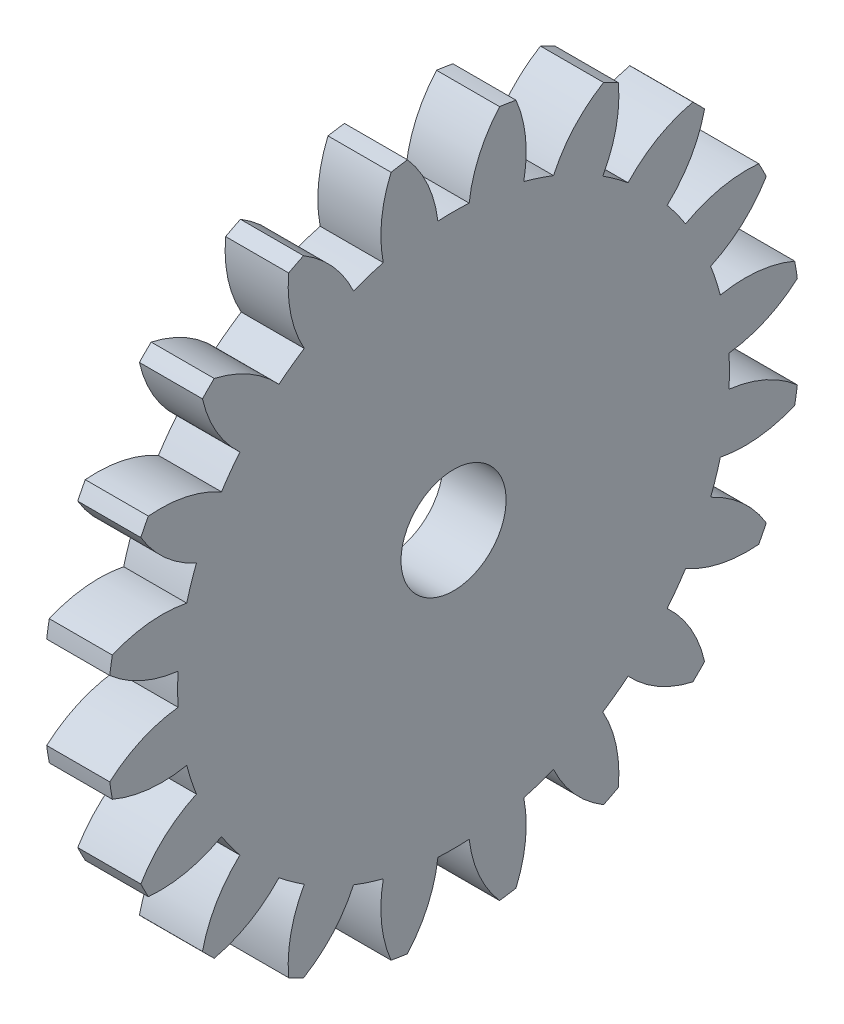
SolidWorks part; units mm, degrees
ref_plane "Plane1" through (0, 0, 0) normal (0, 0, 1) x (1, 0, 0)
ref_plane "Plane2" through (0, 0, 0) normal (0, 1, 0) x (1, 0, 0)
ref_plane "Plane3" through (0, 0, 0) normal (1, 0, 0) x (0, 0, -1)
sketch "HoldingSke" plane through (0, 0, 0) normal (0, 1, 0) x (1, 0, 0)
  line L0 (0, 0) -> (0.6265, -0.228)
  line L1 (-15, 0) -> (100, 0) construction
  line L2 (0, 0) -> (-2.1039, 2.3779)
  line L3 (0, 0) -> (-11.863, 4.5341)
  line L4 (0, 0) -> (8.1152, 2.9537)
  line L5 (0, 0) -> (-46.8476, -17.4728)
  line L6 (0, 0) -> (-2.4869, -1.6779)
  line L7 (-2.1039, 2.3779) -> (8.6586, 51.2059)
  line L8 (-76.2, 54.61) -> (-75.3, 54.61)
  line L9 (-71.009, 38.7566) -> (-53.1078, 45.2721)
  line L10 (-76.2, 71.12) -> (104.1128, 71.12)
  line L11 (0, 0) -> (-3, 0)
  line L12 (-76.2, 101.6) -> (-76.147, 101.6)
  line L13 (24.9733, 27.94) -> (52.9518, 28.4284)
  line L14 (24.9733, 27.94) -> (24.9743, 27.94)
  line L15 (24.9733, 27.94) -> (100.4006, 29.5858)
  line L16 (-63.627, -1.5) -> (-12.827, -1.5)
  circle A0 centre (0, 0) radius 2.5
  circle A1 centre (0, 0) radius 13.124
  circle A2 centre (0, 0) radius 37.5
  circle A3 centre (0, 0) radius 2.5
  dimension "MHD" = 26.248
  dimension "Hub_dia" = 75
  dimension "Bore" = 5
  dimension "MBD" = 5
  dimension "Num_teeth" = 20
  dimension "Pitch" = 0.6667
  dimension "Overall_len" = 50
  dimension "Show_teeth" = 20
  dimension "Thickness" = 3
  dimension "OAL" = 50.0001
  dimension "T_dim" = 0.9
  dimension "Ap" = 20
  dimension "H" = 19.05
  dimension "Pitch_radius" = 180.3128
  dimension "Width" = 3
  dimension "Backlash" = 0.053
  dimension "Addendum_fac" = 1
  dimension "Dedendum_fac" = 1.25
  dimension "Clearance_fac" = 0.25
  dimension "Dedendum_add" = 0.001
  dimension "Module" = 1.5
sketch "BasProSke" plane through (0, 0, 0) normal (0, 1, 0) x (1, 0, 0)
  line L0 (-10, 0) -> (60, 0) construction
  line L1 (0, 0) -> (0, 16.5)
  line L2 (0, 0) -> (3, 0)
  line L3 (3, 0) -> (3, 16.5)
  line L4 (3, 16.5) -> (0, 16.5)
  dimension "Thickness" = 3
  dimension "Diameter" = 33
revolve "Base-Revolve" add sketch "BasProSke" angle 360 about L0
sketch "TooCutSke" plane through (0, 0, 0) normal (1, 0, 0) x (0, 0, -1)
  line L1 (0, 0) -> (0, 107) construction
  line L2 (0, 0) -> (-1.2696, 14.9462) construction
  line L3 (0, 0) -> (-4.6808, 29.5532) construction
  line L4 (-1.2696, 14.9462) -> (-2.3404, 14.7766) construction
  arc A0 (0.7438, 13.1029) -> (-0.7438, 13.1029) centre (0, 0) ccw
  arc A1 (2.21, 16.377) -> (-2.21, 16.377) centre (0, 0) ccw
  circle A2 centre (0, 0) radius 15 construction
  circle A3 centre (0, 0) radius 14.0954 construction
  arc A4 (-0.7438, 13.1029) -> (-2.21, 16.377) centre (-6.7025, 12.3999) ccw
  arc A5 (2.21, 16.377) -> (0.7438, 13.1029) centre (6.7025, 12.3999) ccw
  dimension "Root_dia" = 26.248
  dimension "Overcut_dia" = 33.0508
  dimension "Pitch_dia" = 30
  dimension "Base_dia" = 28.1908
  dimension "Flank_rad" = 6
  dimension "Half_ang" = 9
  dimension "Half_CT" = 1.0841
extrude "ToothCut" cut sketch "TooCutSke" along normal through all
fillet "Breaks" [suppressed] radius 0.03
fillet "RootFillets" [suppressed] radius 0.376
pattern_circular "TeethCuts" count 20 every 18 about axis through (-10, 0, 0) along (1, 0, 0) of "ToothCut", "RootFillets", "Breaks"
sketch "HubNeaOneSke" plane through (0, 0, 0) normal (-1, 0, 0) x (0, 0, 1)
  circle A0 centre (0, 0) radius 13.124
  dimension "Diameter" = 26.248
extrude "HubNearOne" [suppressed] add sketch "HubNeaOneSke" along normal blind 47.0001
sketch "HubNeaBotSke" plane through (0, 0, 0) normal (-1, 0, 0) x (0, 0, 1)
  circle A0 centre (0, 0) radius 13.124
  dimension "Diameter" = 26.248
extrude "HubNearBoth" [suppressed] add sketch "HubNeaBotSke" along normal blind 23.5
ref_plane "FarPln" through (3, 0, 0) normal (1, 0, 0) x (0, 0, -1)
sketch "HubFarSke" plane through (3, 0, 0) normal (1, 0, 0) x (0, 0, -1)
  circle A0 centre (0, 0) radius 13.124
  dimension "Diameter" = 26.248
extrude "HubFar" [suppressed] add sketch "HubFarSke" along normal blind 23.5
sketch "BorSke" plane through (0, 0, 0) normal (1, 0, 0) x (0, 0, -1)
  circle A0 centre (0, 0) radius 2.5
  dimension "Diameter" = 5
extrude "Bore" cut sketch "BorSke" along normal mid plane 100.0001
sketch "KeySke" plane through (0, 0, 0) normal (1, 0, 0) x (0, 0, -1)
  line L0 (-1, 0) -> (-1, 3.4)
  line L1 (-1, 3.4) -> (1, 3.4)
  line L2 (1, 3.4) -> (1, 0)
  line L3 (0, 0) -> (0, 34) construction
  line L4 (-1, 0) -> (1, 0)
  dimension "Offset" = 3.4
  dimension "Width" = 2
extrude "Keyway" [suppressed] cut sketch "KeySke" along normal mid plane 100.0001
pattern_circular "Keyway2" [suppressed] count 2 every 90 about axis through (-10, 0, 0) along (1, 0, 0)
equation "' \"Module@HoldingSke\" = 6.35"
equation "' \"Num_teeth@HoldingSke\" = 12"
equation "' \"Ap@HoldingSke\" =  20"
equation "' \"Ap@HoldingSke\" = 20"
equation "' \"Width@HoldingSke\" = 0.5 * 25.4"
equation "' \"Hub_dia@HoldingSke\"= 1 * 25.4"
equation "' \"Hub_dia@HoldingSke\" = 1 * 25.4"
equation "' \"Overall_len@HoldingSke\" = 1.0 * 25.4"
equation "' \"Bore@HoldingSke\" = 0.75 * 25.4"
equation "' \"T_dim@HoldingSke\" = 0.1 * 25.4"
equation "' \"Width@KeySke\" = 0.25 * 25.4"
equation "' \"Show_teeth@HoldingSke\" = 13"
equation "' \"Backlash@HoldingSke\" = 0.009 * 25.4"
equation "' \"Addendum_fac@HoldingSke\" = 1.0"
equation "' \"Dedendum_fac@HoldingSke\" = 1.25"
equation "' \"Dedendum_add@HoldingSke\" = 0.00005 * 25.4"
equation "' \"Clearance_fac@HoldingSke\" = 0.25"
equation "\"Pitch@HoldingSke\" = 1 / \"Module@HoldingSke\""
equation "\"Overcut_dia@TooCutSke\" = (\"Num_teeth@HoldingSke\" + 2 * \"Addendum_fac@HoldingSke\") / \"Pitch@HoldingSke\" + 0.002 * 25.4"
equation "\"Pitch_dia@TooCutSke\" = \"Num_teeth@HoldingSke\" / \"Pitch@HoldingSke\""
equation "\"Base_dia@TooCutSke\" = \"Num_teeth@HoldingSke\" / \"Pitch@HoldingSke\" * cos((\"Ap@HoldingSke\"  * 3.14159265 / 180))"
equation "\"Root_dia@TooCutSke\" = (\"Num_teeth@HoldingSke\" + 2) / \"Pitch@HoldingSke\" - 2 * (\"Addendum_fac@HoldingSke\" + \"Dedendum_fac@HoldingSke\") / \"Pitch@HoldingSke\" - \"Dedendum_add@HoldingSke\" * 2"
equation "\"Half_ang@TooCutSke\" = 180 / \"Num_teeth@HoldingSke\""
equation "\"Half_CT@TooCutSke\" = \"Num_teeth@HoldingSke\" / \"Pitch@HoldingSke\" * sin((3.14159265 / 2 / \"Num_teeth@HoldingSke\")) / 2 - 7 * \"Backlash@HoldingSke\" / 4"
equation "\"Flank_rad@TooCutSke\" = \"Num_teeth@HoldingSke\" / \"Pitch@HoldingSke\" / 5"
equation "\"Radius@RootFillets\" = \"Clearance_fac@HoldingSke\" / \"Pitch@HoldingSke\" + \"Dedendum_add@HoldingSke\""
equation "\"Break_rad@Breaks\" = 0.02 / \"Pitch@HoldingSke\""
equation "\"Thickness@HoldingSke\" = \"Width@HoldingSke\""
equation "\"OAL@HoldingSke\" = \"Thickness@HoldingSke\""
equation "\"MHD@HoldingSke\" = (\"Num_teeth@HoldingSke\" + 2) / \"Pitch@HoldingSke\" - 2 * (\"Addendum_fac@HoldingSke\" + \"Dedendum_fac@HoldingSke\")  / \"Pitch@HoldingSke\" - \"Dedendum_add@HoldingSke\" * 2"
equation "\"MBD@HoldingSke\" = (\"Num_teeth@HoldingSke\" + 2) / \"Pitch@HoldingSke\" - 2 * (\"Addendum_fac@HoldingSke\" + \"Dedendum_fac@HoldingSke\")  / \"Pitch@HoldingSke\" - \"Dedendum_add@HoldingSke\" * 2 - 0.002 * 25.4"
equation "\"MHD@HoldingSke\" = ((sgn( \"MHD@HoldingSke\" - \"Hub_dia@HoldingSke\" )-1)*( \"MHD@HoldingSke\" - \"Hub_dia@HoldingSke\" ))/-2+ \"Hub_dia@HoldingSke\""
equation "\"MBD@HoldingSke\" = ((sgn( \"MBD@HoldingSke\" - \"Bore@HoldingSke\" )-1)*( \"MBD@HoldingSke\" - \"Bore@HoldingSke\" ))/-2+ \"Bore@HoldingSke\""
equation "\"OAL@HoldingSke\" = ((sgn( \"OAL@HoldingSke\" - \"Overall_len@HoldingSke\" )+1)*( \"OAL@HoldingSke\" - \"Overall_len@HoldingSke\" ))/2 + \"Overall_len@HoldingSke\" + 0.000002 * 25.4"
equation "\"Num_teeth@TeethCuts\" = int( \"Show_teeth@HoldingSke\" ) + 1"
equation "\"Num_teeth@TeethCuts\" = ((sgn( \"Num_teeth@TeethCuts\" - \"Num_teeth@HoldingSke\" )-1)*( \"Num_teeth@TeethCuts\" - \"Num_teeth@HoldingSke\" ))/-2+ \"Num_teeth@HoldingSke\""
equation "\"Num_teeth@TeethCuts\" = ((sgn( \"Num_teeth@TeethCuts\" - 2.0)+1)*( \"Num_teeth@TeethCuts\" - 2.0))/2 +2.0"
equation "\"Angle@TeethCuts\" = 360.0 / \"Num_teeth@HoldingSke\""
equation "\"Diameter@BasProSke\" = (\"Num_teeth@HoldingSke\" + 2 * \"Addendum_fac@HoldingSke\") / \"Pitch@HoldingSke\""
equation "\"Thickness@BasProSke\"  = \"Thickness@HoldingSke\""
equation "' \"Fillet_rad@BasProSke\" =  \"Thickness@HoldingSke\" * 0.05"
equation "' \"Fillet_rad@BasProSke\" = \"Thickness@HoldingSke\" * 0.05"
equation "\"MHD@HoldingSke\" = ((sgn( \"MHD@HoldingSke\" - \"Root_dia@TooCutSke\" )-1)*( \"MHD@HoldingSke\" - \"Root_dia@TooCutSke\" ))/-2+ \"Root_dia@TooCutSke\""
equation "\"Diameter@HubNeaOneSke\" = \"MHD@HoldingSke\""
equation "\"Length@HubNearOne\" = \"OAL@HoldingSke\" - \"Thickness@BasProSke\""
equation "\"Diameter@HubNeaBotSke\" = \"MHD@HoldingSke\""
equation "\"Length@HubNearBoth\" = ( \"OAL@HoldingSke\" - \"Thickness@BasProSke\" ) / 2.0"
equation "\"Thickness@FarPln\" = \"Thickness@BasProSke\""
equation "\"Diameter@HubFarSke\" = \"MHD@HoldingSke\""
equation "\"Length@HubFar\" = ( \"OAL@HoldingSke\" - \"Thickness@BasProSke\" ) / 2.0"
equation "\"Diameter@BorSke\" = \"MBD@HoldingSke\""
equation "\"D1@Bore\" = \"OAL@HoldingSke\" * 2.0"
equation "\"D1@Keyway\" = \"OAL@HoldingSke\" * 2.0"
equation "\"Offset@KeySke\" = \"T_dim@HoldingSke\" + \"MBD@HoldingSke\" / 2.0"
